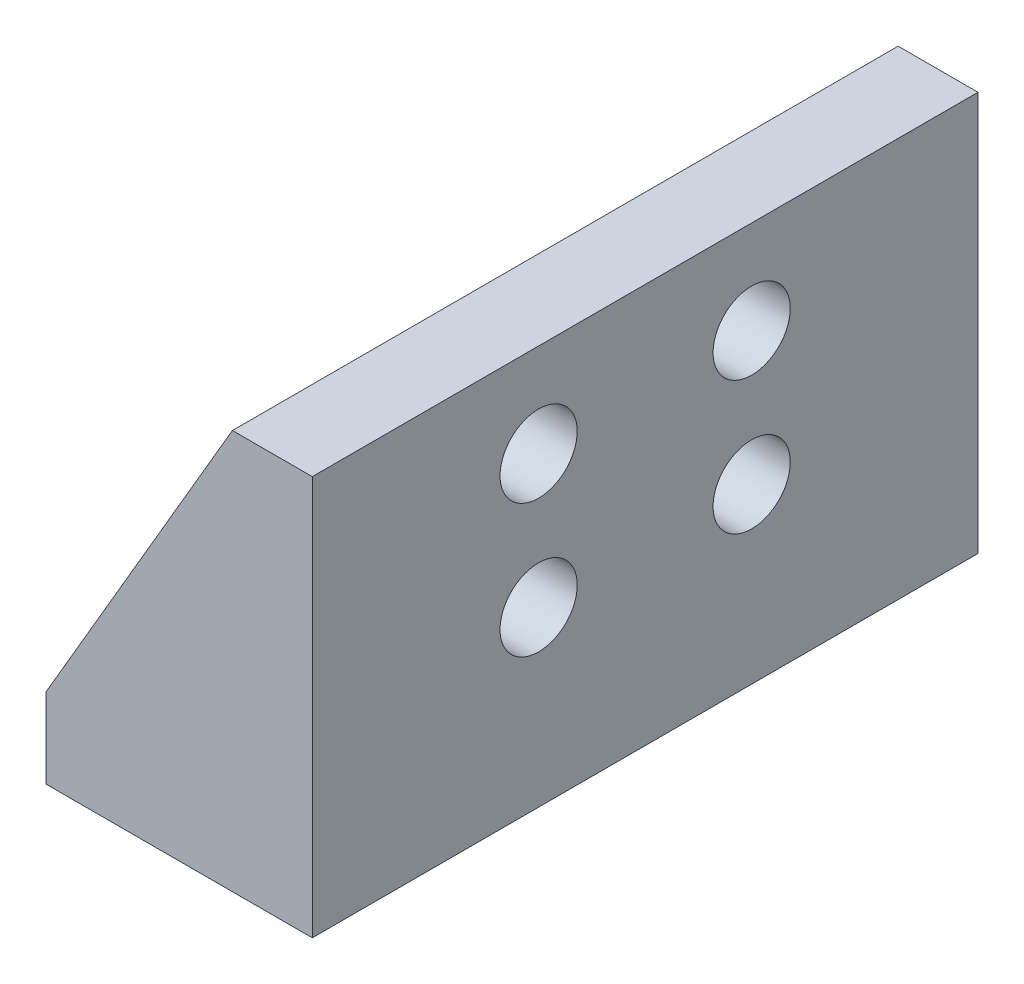
SolidWorks part; units mm, degrees
ref_plane "前视基准面" through (0, 0, 0) normal (0, 0, 1) x (1, 0, 0)
ref_plane "上视基准面" through (0, 0, 0) normal (0, 1, 0) x (1, 0, 0)
ref_plane "右视基准面" through (0, 0, 0) normal (1, 0, 0) x (0, 0, -1)
sketch "草图3" plane through (0, 0, 0) normal (0, 0, 1) x (1, 0, 0)
  line L0 (0, 0) -> (10, 0)
  line L1 (10, 0) -> (10, 15)
  line L2 (0, 0) -> (0, 3)
  line L3 (0, 3) -> (7, 3)
  line L4 (7, 3) -> (7, 15)
  line L5 (7, 15) -> (10, 15)
  dimension "D1" = 10
  dimension "D2" = 15
  dimension "D3" = 3
  dimension "D4" = 3
extrude "凸台-拉伸2" add sketch "草图3" against normal blind 25
sketch "草图4" plane through (0, 0, 0) normal (0, 0, 1) x (1, 0, 0)
  line L0 (7, 15) -> (0, 3)
  line L1 (7, 3) -> (0, 3) construction
  line L8 (0, 3) -> (0, 0)
  line L9 (0, 0) -> (10, 0)
  line L10 (10, 0) -> (10, 15)
  line L11 (10, 15) -> (7, 15)
  line L12 (7, 15) -> (7, 3)
  line L13 (7, 3) -> (0, 3)
  line L18 (7, 15) -> (7, 3)
  line L19 (7, 3) -> (0, 3)
  dimension "D1" = 0
extrude "凸台-拉伸3" add sketch "草图4" against normal blind 5
sketch "草图5" plane through (0, 0, -25) normal (0, 0, -1) x (-1, 0, 0)
  line L0 (-7, 15) -> (0, 3)
  line L1 (-7, 15) -> (-7, 3)
  line L2 (-7, 3) -> (0, 3)
extrude "凸台-拉伸5" add sketch "草图5" against normal blind 5
sketch "草图8" plane through (7, 0, 0) normal (-1, 0, 0) x (0, 0, 1)
  line L0 (-12.5, 15) -> (-12.5, 3) construction
  line L1 (-20, 15) -> (-5, 15) construction
  line L2 (-20, 3) -> (-5, 3) construction
  line L3 (-16.5, 15) -> (-16.5, 3) construction
  line L4 (-8.5, 15) -> (-8.5, 3) construction
  line L5 (-20, 11.5) -> (-5, 11.5) construction
  line L6 (-20, 15) -> (-20, 3) construction
  line L7 (-5, 15) -> (-5, 3) construction
  line L8 (-20, 6.5) -> (-5, 6.5) construction
  line L9 (-20, 3) -> (-20, 15) construction
  line L10 (-5, 3) -> (-5, 15) construction
  circle A0 centre (-16.5, 11.5) radius 1.45
  circle A1 centre (-16.5, 6.5) radius 1.45
  circle A2 centre (-8.5, 6.5) radius 1.45
  circle A3 centre (-8.5, 11.5) radius 1.45
  dimension "D5" = 2.9
  dimension "D1" = 3.5
  dimension "D2" = 3.5
  dimension "D3" = 3.5
  dimension "D4" = 3.5
extrude "切除-拉伸3" cut sketch "草图8" against normal blind 300 contours A0 | A1 | A3 | A2
sketch "草图9" plane through (0, 3, 0) normal (0, 1, 0) x (1, 0, 0)
  line L0 (3.5, 20) -> (3.5, 5) construction
  line L1 (7, 20) -> (0, 20) construction
  line L2 (7, 5) -> (0, 5) construction
  line L3 (7, 12.5) -> (0, 12.5) construction
  line L4 (7, 20) -> (7, 5) construction
  line L5 (0, 20) -> (0, 5) construction
  line L6 (7, 16.25) -> (0, 16.25) construction
  line L7 (7, 20) -> (7, 5) construction
  line L8 (7, 8.75) -> (0, 8.75) construction
  circle A0 centre (3.5, 16.25) radius 1.45
  circle A1 centre (3.5, 8.75) radius 1.45
  dimension "D2" = 2.9
  dimension "D1" = 3.75
extrude "切除-拉伸4" cut sketch "草图9" against normal blind 300
sketch "草图10" plane through (0, 3, 0) normal (0, 1, 0) x (1, 0, 0)
  circle A0 centre (3.5, 16.25) radius 2.6
  circle A1 centre (3.5, 8.75) radius 2.6
  dimension "D1" = 5.2
  dimension "D2" = 5.2
extrude "切除-拉伸5" cut sketch "草图10" against normal blind 2
